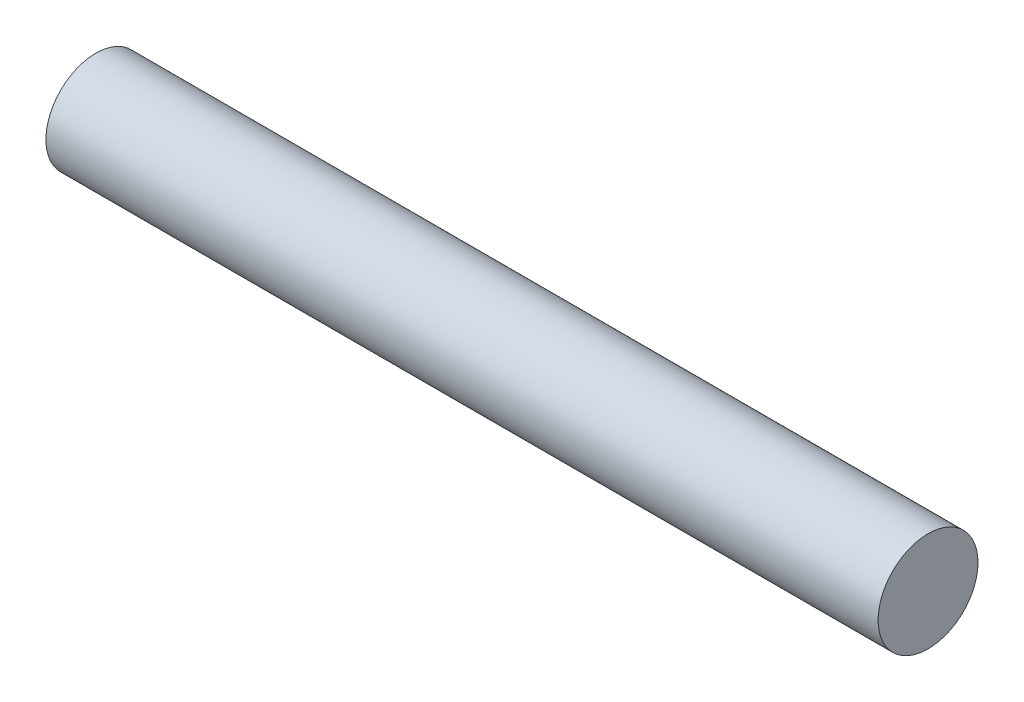
SolidWorks part; units mm, degrees
material "AISI 304"
ref_plane "前视基准面" through (0, 0, 0) normal (0, 0, 1) x (1, 0, 0)
ref_plane "上视基准面" through (0, 0, 0) normal (0, 1, 0) x (1, 0, 0)
ref_plane "右视基准面" through (0, 0, 0) normal (1, 0, 0) x (0, 0, -1)
sketch "Sketch1" plane through (0, 0, 0) normal (1, 0, 0) x (0, 0, -1)
  circle A0 centre (0, 0) radius 3
  dimension "D1" = 6
extrude "Boss-Extrude1" add sketch "Sketch1" along normal blind 50
